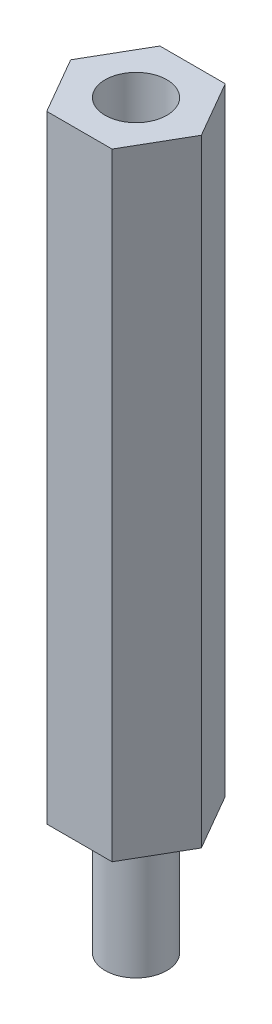
SolidWorks part; units mm, degrees
material "Plain Carbon Steel"
ref_plane "Front Plane" through (0, 0, 0) normal (0, 0, 1) x (1, 0, 0)
ref_plane "Top Plane" through (0, 0, 0) normal (0, 1, 0) x (1, 0, 0)
ref_plane "Right Plane" through (0, 0, 0) normal (1, 0, 0) x (0, 0, -1)
sketch "Sketch1" plane through (0, 0, 0) normal (0, 1, 0) x (1, 0, 0)
  line L1 (3.1754, 0) -> (1.5877, 2.75)
  line L2 (1.5877, 2.75) -> (-1.5877, 2.75)
  line L3 (-1.5877, 2.75) -> (-3.1754, 0)
  line L4 (-3.1754, 0) -> (-1.5877, -2.75)
  line L5 (-1.5877, -2.75) -> (1.5877, -2.75)
  line L6 (1.5877, -2.75) -> (3.1754, 0)
  circle A0 centre (0, 0) radius 2.75 construction
  dimension "D1" = 5.5
extrude "Boss-Extrude1" add sketch "Sketch1" along normal blind 30
sketch "Sketch2" plane through (0, 30, 0) normal (0, 1, 0) x (1, 0, 0)
  circle A0 centre (0, 0) radius 1.5
  dimension "D1" = 3
extrude "Cut-Extrude1" cut sketch "Sketch2" against normal blind 12
sketch "Sketch3" plane through (0, 0, 0) normal (0, -1, 0) x (-1, 0, 0)
  circle A0 centre (0, 0) radius 1.5
  point P3 (-0.9467, 0.575)
extrude "Boss-Extrude2" add sketch "Sketch3" along normal blind 6
